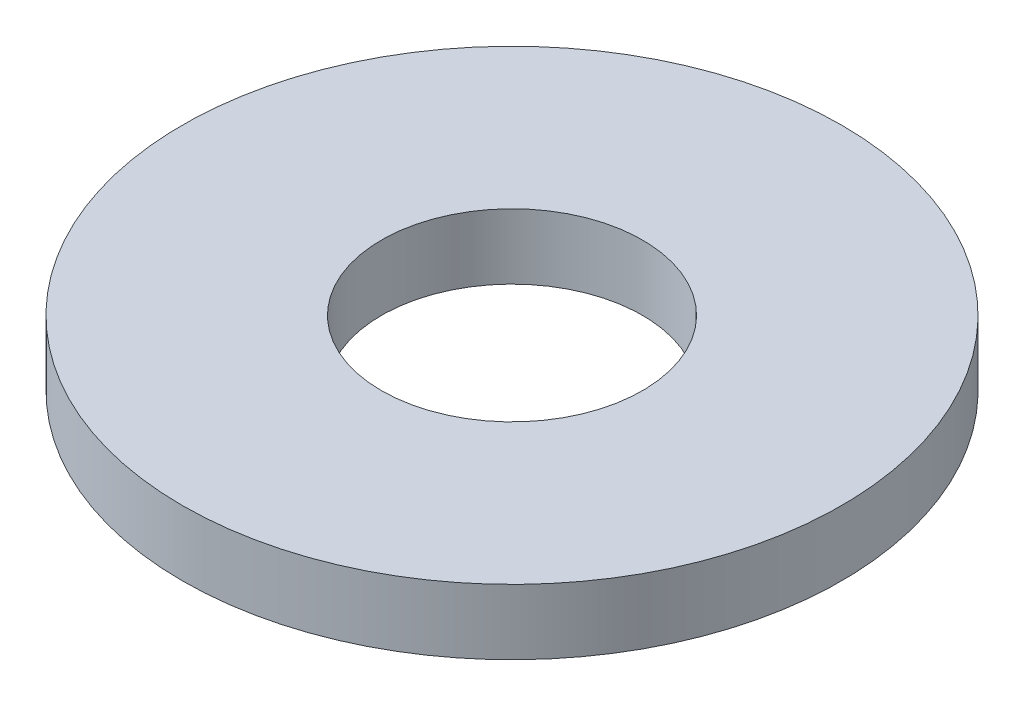
SolidWorks part; units mm, degrees
ref_plane "正面" through (0, 0, 0) normal (0, 0, 1) x (1, 0, 0)
ref_plane "平面" through (0, 0, 0) normal (0, 1, 0) x (1, 0, 0)
ref_plane "右側面" through (0, 0, 0) normal (1, 0, 0) x (0, 0, -1)
sketch "ｽｹｯﾁ1" plane through (0, 0, 0) normal (0, 1, 0) x (1, 0, 0)
  circle A0 centre (0, 0) radius 5.05
  circle A1 centre (0, 0) radius 2
  dimension "D1" = 4
  dimension "D2" = 10.1
extrude "押し出し1" add sketch "ｽｹｯﾁ1" along normal blind 1
